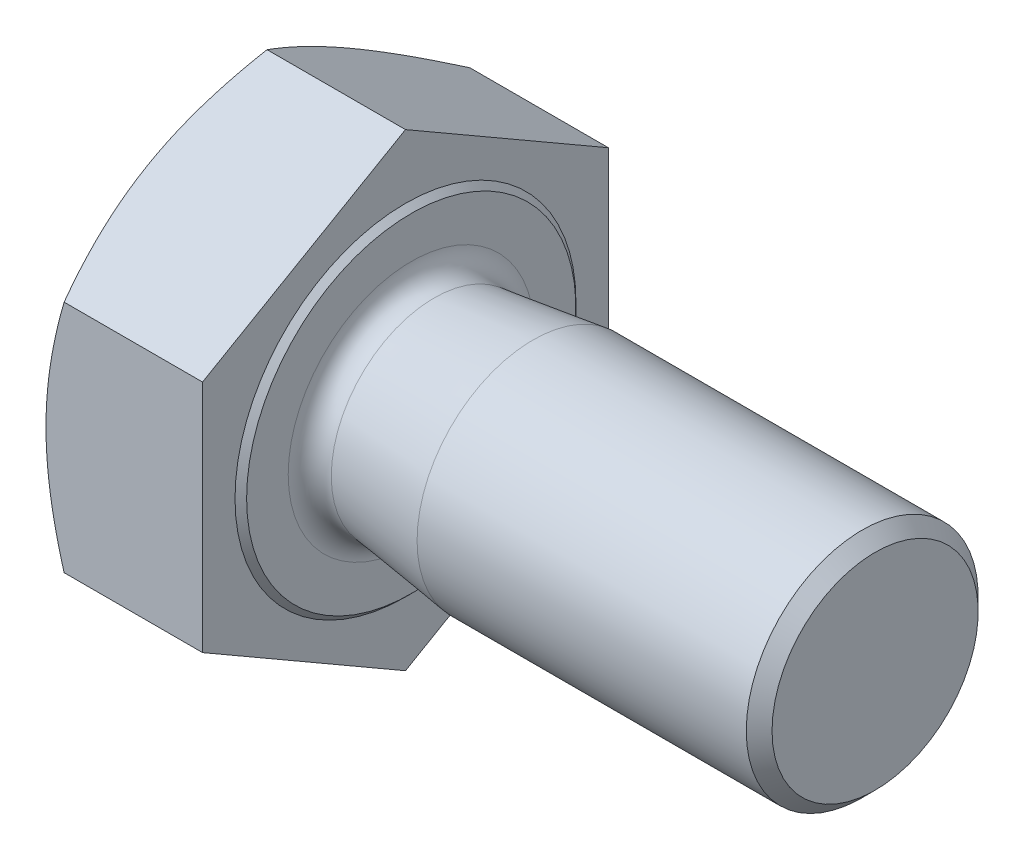
SolidWorks part; units mm, degrees
ref_plane "前视基准面" through (0, 0, 0) normal (0, 0, 1) x (1, 0, 0)
ref_plane "上视基准面" through (0, 0, 0) normal (0, 1, 0) x (1, 0, 0)
ref_plane "右视基准面" through (0, 0, 0) normal (1, 0, 0) x (0, 0, -1)
sketch "草图1" plane through (0, 0, 0) normal (0, 0, 1) x (1, 0, 0)
  line L0 (0, 0) -> (10.8, 0) construction
  line L1 (0, 0) -> (0, 3.83)
  line L2 (0, 3.83) -> (2.8, 3.83)
  line L3 (2.8, 3.83) -> (2.8, 0)
  line L4 (2.8, 2) -> (10.8, 2)
  line L5 (10.8, 2) -> (10.8, 0)
  line L6 (0, 3.5) -> (0.1905, 3.83)
  line L7 (9.4, 2) -> (9.4, 0)
  line L8 (4.9, 2) -> (4.9, 0)
  line L9 (2.8, 1.7727) -> (10.8, 1.7727)
  line L10 (10.8, 1.6211) -> (2.8, 1.6211)
  line L11 (2.7, 2.94) -> (2.8, 2.84)
  line L12 (2.7, 3.83) -> (2.7, 0)
  line L13 (2.7, 2.94) -> (2.7, 0) construction
  arc A0 (2.8, 2.35) -> (3.15, 2) centre (3.15, 2.35) ccw
  point P12 (10.1, 0)
  point P13 (0.93, 3.83)
  point P14 (2.8, 2.35)
  point P24 (2.8, 2.94)
  dimension "D1" = 0.1
  dimension "r" = 0.35
  dimension "k" = 2.8
  dimension "D2" = 45
  dimension "β" = 30
  dimension "e" = 7.66
  dimension "s" = 7
  dimension "d" = 4
  dimension "l" = 8
  dimension "D52" = 1.4
  dimension "P" = 0.7
  dimension "kw" = 1.87
  dimension "da" = 4.7
  dimension "a" = 2.1
  dimension "ds" = 3.5454
  dimension "D61" = 3.2422
  dimension "dw" = 5.88
  dimension "c" = 0.1
sketch "草图2" plane through (0, 0, 0) normal (1, 0, 0) x (0, 0, -1)
  line L1 (0, 4.0415) -> (-3.5, 2.0207)
  line L2 (-3.5, 2.0207) -> (-3.5, -2.0207)
  line L3 (-3.5, -2.0207) -> (0, -4.0415)
  line L4 (0, -4.0415) -> (3.5, -2.0207)
  line L5 (3.5, -2.0207) -> (3.5, 2.0207)
  line L6 (3.5, 2.0207) -> (0, 4.0415)
  circle A0 centre (0, 0) radius 3.5 construction
sketch "草图3" plane through (0, 0, 0) normal (1, 0, 0) x (0, 0, -1)
  line L0 (3.5, 2.0207) -> (0, 4.0415) construction
  line L1 (0, 4.0415) -> (-3.5, 2.0207) construction
  line L2 (-3.5, 2.0207) -> (-3.5, -2.0207) construction
  line L3 (3.5, -2.0207) -> (3.5, 2.0207) construction
  line L4 (0, -4.0415) -> (3.5, -2.0207) construction
  line L5 (-3.5, -2.0207) -> (0, -4.0415) construction
  line L6 (3.5, 2.0207) -> (0, 4.0415)
  line L7 (0, 4.0415) -> (-3.5, 2.0207)
  line L8 (-3.5, 2.0207) -> (-3.5, -2.0207)
  line L9 (3.5, -2.0207) -> (3.5, 2.0207)
  line L10 (0, -4.0415) -> (3.5, -2.0207)
  line L11 (-3.5, -2.0207) -> (0, -4.0415)
extrude "凸台-拉伸1" add sketch "草图3" along normal up to vertex (2.8 mm away) up to point (2.8, 3.83, 0)
sketch "草图4" plane through (0, 0, 0) normal (-1, 0, 0) x (0, 0, 1)
  circle A0 centre (0, 0) radius 3.5 construction
  circle A1 centre (0, 0) radius 3.5
  circle A2 centre (0, 0) radius 7.66
  dimension "D1" = 15.32
extrude "切除-拉伸1" cut sketch "草图4" against normal blind 0.35 draft 60
sketch "草图5" [suppressed] plane through (0, 0, 0) normal (0, 0, 1) x (1, 0, 0)
  line L0 (33, 26) -> (233, 26) construction
  line L1 (233, 26) -> (233, 0) construction
  line L2 (0, 0) -> (233, 0) construction
  line L3 (35.3, 26) -> (233, 26)
  line L4 (233, 26) -> (233, 0)
  line L5 (33, 0) -> (233, 0)
  line L6 (33, 28.3) -> (33, 0)
  arc A0 (33, 28.3) -> (35.3, 26) centre (35.3, 28.3) ccw construction
  arc A1 (33, 28.3) -> (35.3, 26) centre (35.3, 28.3) ccw
revolve "旋转1" [suppressed] add sketch "草图5" angle 360 about L5
cosmetic thread "装饰螺纹线2" [suppressed] parameters "D1"=5.9, "D2"=3.2422
chamfer "倒角2" [suppressed] distance 0.2222 angle 45
sketch "草图7" [suppressed] plane through (0, 0, 0) normal (0, 0, 1) x (1, 0, 0)
  line L0 (33, 37) -> (32, 38)
  line L1 (32, 38) -> (32, 88.25)
  line L2 (32, 88.25) -> (33, 88.25)
  line L3 (33, 88.25) -> (33, 37)
  line L4 (0, 0) -> (233, 0) construction
  line L5 (0, 0) -> (233, 0) construction
  dimension "D1" = 15.32
revolve "切除-旋转1" [suppressed] cut sketch "草图7" angle 360 mid plane about L5
sketch "草图6" plane through (0, 0, 0) normal (0, 0, 1) x (1, 0, 0)
  line L0 (4.9, 0) -> (4.9, 2) construction
  line L1 (4.9, 2) -> (10.8, 2)
  line L2 (10.8, 2) -> (10.8, 0)
  line L3 (4.9, 2) -> (3.1957, 1.7757)
  line L5 (2.8, 1.7727) -> (10.8, 1.7727) construction
  line L6 (2.8, 3.83) -> (2.8, 0) construction
  line L7 (2.8, 2.1227) -> (2.8, 0)
  line L8 (2.8, 0) -> (10.8, 0)
  arc A0 (3.1957, 1.7757) -> (2.8, 2.1227) centre (3.15, 2.1227) cw
  arc A1 (2.8, 2.35) -> (3.15, 2) centre (3.15, 2.35) ccw construction
revolve "旋转2" add sketch "草图6" angle 360 about L8
cosmetic thread "装饰螺纹线1" parameters "D1"=5.9, "D2"=3.2422
chamfer "倒角1" distance 0.2222 angle 45 1 edges at (10.8, 0, 2)
sketch "草图8" plane through (0, 0, 0) normal (0, 0, 1) x (1, 0, 0)
  line L0 (2.8, 2.84) -> (2.7, 2.94)
  line L1 (2.7, 2.94) -> (2.7, 7.66)
  line L2 (2.7, 7.66) -> (2.8, 7.66)
  line L3 (2.8, 7.66) -> (2.8, 2.84)
  line L4 (0, 0) -> (10.8, 0) construction
  line L5 (0, 0) -> (10.8, 0) construction
  dimension "D1" = 15.32
revolve "切除-旋转2" cut sketch "草图8" angle 360 mid plane about L5
